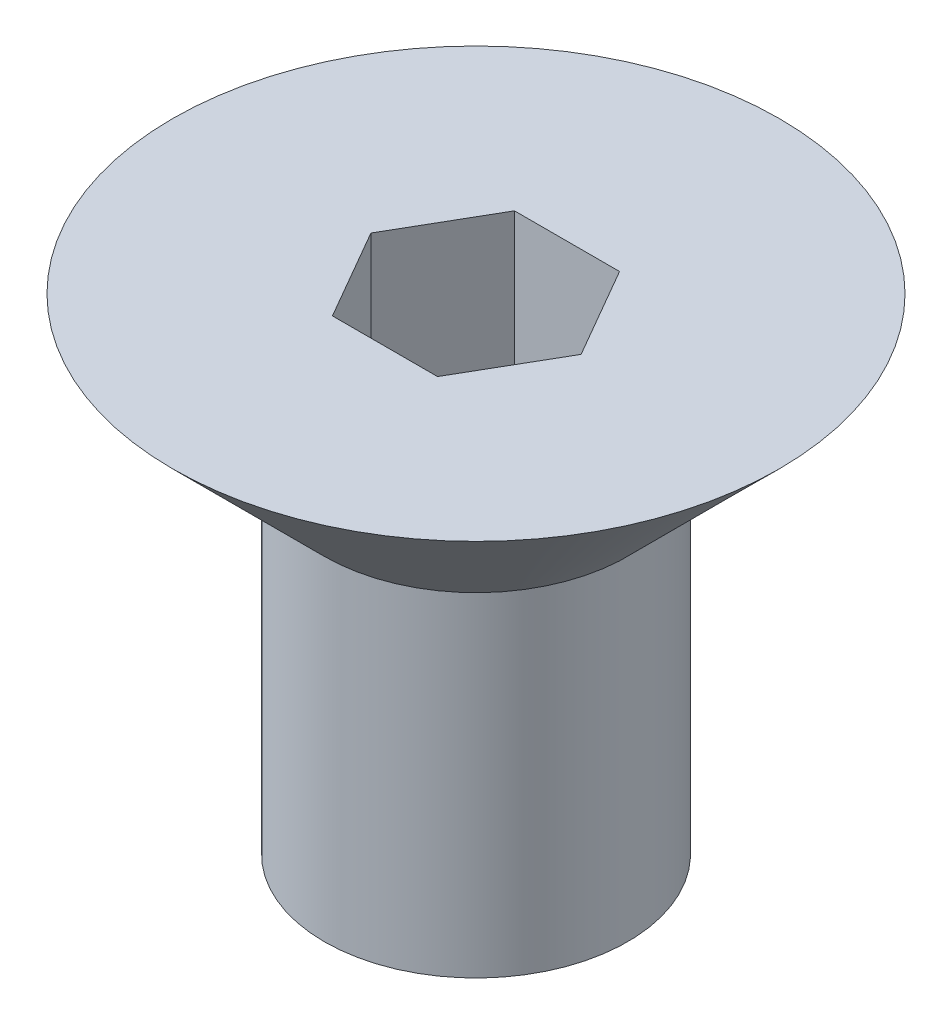
SolidWorks part; units mm, degrees
material "AISI 304"
ref_plane "Front Plane" through (0, 0, 0) normal (0, 0, 1) x (1, 0, 0)
ref_plane "Top Plane" through (0, 0, 0) normal (0, 1, 0) x (1, 0, 0)
ref_plane "Right Plane" through (0, 0, 0) normal (1, 0, 0) x (0, 0, -1)
sketch "Sketch1" plane through (0, 0, 0) normal (0, 0, 1) x (1, 0, 0)
  line L0 (0, 61.6916) -> (0, -59.3578) construction
  line L1 (0, -16) -> (5, -16)
  line L2 (5, -16) -> (5, -5)
  line L3 (-6.7326, -3.2674) -> (-5, -5) construction
  line L5 (10, 0) -> (0, 0)
  line L6 (0, 0) -> (0, -16)
  line L7 (5, -5) -> (10, 0)
  dimension "D1" = 90
  dimension "D2" = 20
  dimension "D3" = 10
  dimension "D5" = 16
revolve "Revolve1" add sketch "Sketch1" angle 360 about L0
sketch "Sketch2" plane through (0, 0, 0) normal (0, 1, 0) x (-1, 0, 0)
  line L1 (-1.7321, -3) -> (1.7321, -3)
  line L2 (1.7321, -3) -> (3.4641, 0)
  line L3 (3.4641, 0) -> (1.7321, 3)
  line L4 (1.7321, 3) -> (-1.7321, 3)
  line L5 (-1.7321, 3) -> (-3.4641, 0)
  line L6 (-3.4641, 0) -> (-1.7321, -3)
  circle A0 centre (0, 0) radius 3 construction
  dimension "D1" = 6
extrude "Cut-Extrude1" cut sketch "Sketch2" against normal blind 5
